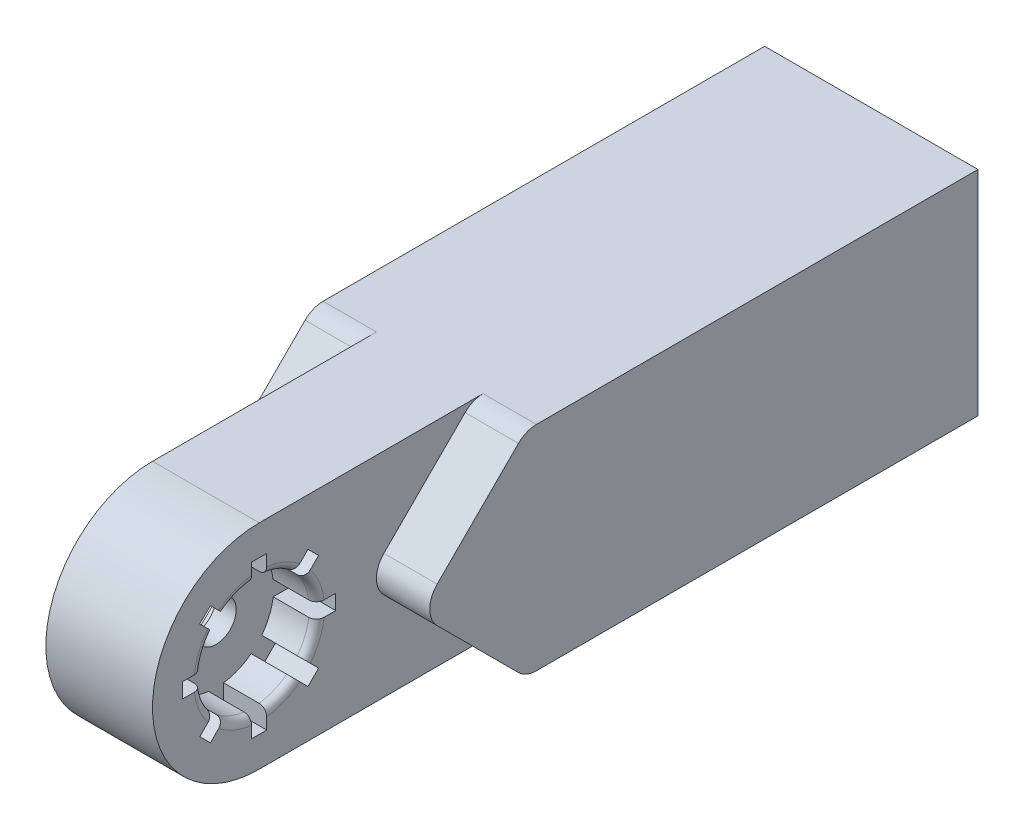
SolidWorks part; units mm, degrees
ref_plane "Front Plane" through (0, 0, 0) normal (0, 0, 1) x (1, 0, 0)
ref_plane "Top Plane" through (0, 0, 0) normal (0, 1, 0) x (1, 0, 0)
ref_plane "Right Plane" through (0, 0, 0) normal (1, 0, 0) x (0, 0, -1)
sketch "Sketch2" plane through (0, 0, 0) normal (0, 0, 1) x (1, 0, 0)
  line L1 (-21, 21) -> (21, 21)
  line L2 (-21, 21) -> (-21, -21)
  line L3 (-21, -21) -> (21, -21)
  line L4 (21, 21) -> (21, -21)
  line L5 (-21, 21) -> (21, -21) construction
  line L6 (-21, -21) -> (21, 21) construction
  point P0 (0, 0)
  dimension "D1" = 42
  dimension "D2" = 42
extrude "Boss-Extrude1" add sketch "Sketch2" along normal blind 89
ref_plane "Plane1" through (0, 0, 89) normal (0, 0, 1) x (1, 0, 0)
sketch "Sketch3" plane through (0, 0, 89) normal (0, 0, 1) x (1, 0, 0)
  line L0 (21, 21) -> (-21, 21) construction
  line L1 (10.5, -21) -> (-10.5, -21)
  line L2 (10.5, -21) -> (10.5, 21)
  line L3 (10.5, 21) -> (-10.5, 21)
  line L4 (-10.5, -21) -> (-10.5, 21)
  line L5 (10.5, -21) -> (-10.5, 21) construction
  line L6 (10.5, 21) -> (-10.5, -21) construction
  point P0 (0, 0)
  dimension "D1" = 21
ref_plane "Plane4" through (0, 0, 0) normal (0, 0, -1) x (-1, 0, 0)
sketch "Sketch7" plane through (0, 0, 0) normal (0, 0, -1) x (-1, 0, 0)
  line L0 (21, 21) -> (21, -21) construction
  line L1 (-16, 16) -> (16, 16)
  line L2 (-16, 16) -> (-16, -16)
  line L3 (-16, -16) -> (16, -16)
  line L4 (16, 16) -> (16, -16)
  line L5 (-16, 16) -> (16, -16) construction
  line L6 (-16, -16) -> (16, 16) construction
  line L7 (-21, 21) -> (21, 21) construction
  point P0 (0, 0)
  dimension "D1" = 5
  dimension "D2" = 5
extrude "Cut-Extrude1" cut sketch "Sketch7" against normal blind 81 contours L4 L3 L2 L1
extrude "Boss-Extrude2" add sketch "Sketch3" along normal blind 42
ref_plane "Plane5" through (-10.5, 0, 0) normal (-1, 0, 0) x (0, 0, 1)
sketch "Sketch8" plane through (-10.5, 0, 0) normal (-1, 0, 0) x (0, 0, 1)
  line L0 (131, 21) -> (131, -21) construction
  line L1 (131, 21) -> (131, -21)
  arc A0 (131, 21) -> (131, -21) centre (131, 0) cw
  dimension "D1" = 21
extrude "Boss-Extrude3" add sketch "Sketch8" against normal blind 21
ref_plane "Plane6" through (-10.5, 0, 0) normal (-1, 0, 0) x (0, 0, 1)
sketch "Sketch9" plane through (-10.5, 0, 0) normal (-1, 0, 0) x (0, 0, 1)
  line L0 (89, 21) -> (89, -21) construction
  line L1 (131, 21) -> (131, -21)
  circle A0 centre (131, 0) radius 11.35
  dimension "D1" = 42
  dimension "D2" = 22.7
extrude "Cut-Extrude2" cut sketch "Sketch9" against normal blind 8.5 contours A0
ref_plane "Plane7" through (10.5, 0, 0) normal (1, 0, 0) x (0, 0, -1)
sketch "Sketch11" plane through (10.5, 0, 0) normal (1, 0, 0) x (0, 0, -1)
  line L0 (-131, 21) -> (-131, -21)
  circle A0 centre (-131, 0) radius 11.35
  dimension "D1" = 22.7
extrude "Cut-Extrude3" cut sketch "Sketch11" against normal blind 8.5 contours A0
ref_plane "Plane8" through (-2, 0, 0) normal (-1, 0, 0) x (0, 0, 1)
sketch "Sketch12" plane through (-2, 0, 0) normal (-1, 0, 0) x (0, 0, 1)
  circle A0 centre (131, 0) radius 3.975
  dimension "D1" = 7.95
extrude "Cut-Extrude4" cut sketch "Sketch12" against normal through all
ref_plane "Plane10" through (-2, 0, 0) normal (-1, 0, 0) x (0, 0, 1)
ref_plane "Plane11" through (-10.5, 0, 0) normal (-1, 0, 0) x (0, 0, 1)
sketch "Sketch20" plane through (-10.5, 0, 0) normal (-1, 0, 0) x (0, 0, 1)
  line L0 (131, 0) -> (110, 0)
  line L1 (110, 0) -> (110, 21)
  line L2 (110, 0) -> (110, -21)
  line L4 (110, 21) -> (89, 21)
  line L6 (110, -21) -> (89, -21)
  line L7 (89, 21) -> (110, 0)
  line L8 (89, -21) -> (110, 0)
  line L9 (89, 21) -> (89, -21)
  circle A0 centre (131, 0) radius 11.35
  dimension "D1" = 21
extrude "Boss-Extrude4" add sketch "Sketch20" along normal blind 10.5 and the other way blind 31.5 contours L7 L9 L8
fillet "Fillet1" radius 5 1 edges at (15.75, 0, 110)
fillet "Fillet2" radius 5 1 edges at (-15.75, 0, 110)
fillet "Fillet3" radius 5 1 edges at (-15.75, -21, 89)
fillet "Fillet4" radius 5 1 edges at (-15.75, 21, 89)
fillet "Fillet5" radius 5 1 edges at (15.75, -21, 89)
fillet "Fillet6" radius 5 1 edges at (15.75, 21, 89)
fillet "Fillet7" radius 1.5 1 edges at (-10.5, 0, 142.35)
fillet "Fillet8" radius 1.5 1 edges at (10.5, 0, 119.65)
sketch "Sketch21" plane through (-10.5, 0, 0) normal (-1, 0, 0) x (0, 0, 1)
  line L1 (129.5207, 10.6415) -> (132.4793, 10.6415)
  line L2 (129.5207, 10.6415) -> (129.5207, 15.0585)
  line L3 (129.5207, 15.0585) -> (132.4793, 15.0585)
  line L4 (132.4793, 10.6415) -> (132.4793, 15.0585)
  line L5 (129.5207, 10.6415) -> (132.4793, 15.0585) construction
  line L6 (129.5207, 15.0585) -> (132.4793, 10.6415) construction
  circle A0 centre (131, 0) radius 12.85 construction
  point P0 (131, 12.85)
  dimension "D1" = 4.417
extrude "Cut-Extrude5" cut sketch "Sketch21" against normal blind 8.5
pattern_circular "CirPattern2" count 8 over 360 about axis through (0, 0, 131) along (1, 0, 0) of "Cut-Extrude5"
ref_plane "Plane12" through (0, 21, 0) normal (0, 1, 0) x (1, 0, 0)
ref_plane "Plane13" through (10.5, 0, 0) normal (1, 0, 0) x (0, 0, -1)
ref_plane "Plane14" through (0, 0, 0) normal (1, 0, 0) x (0, 0, -1)
mirror "Mirror1" about plane through (0, 0, 0) normal (1, 0, 0) of "CirPattern2", "Cut-Extrude5"
